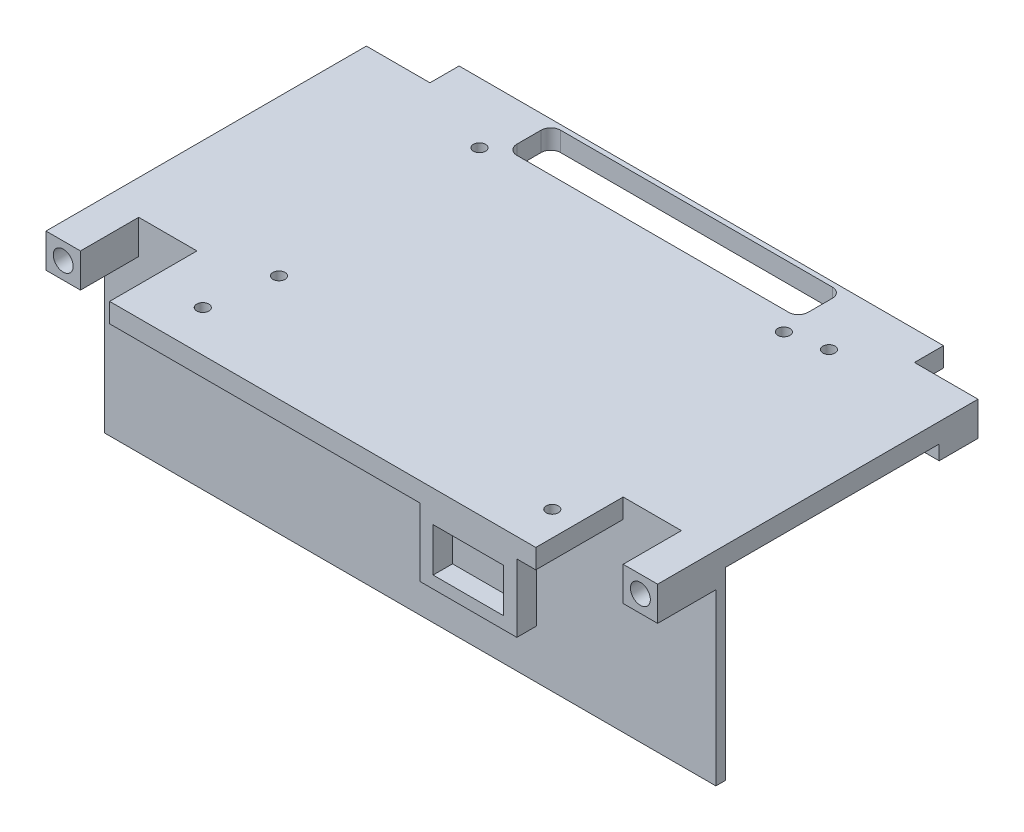
SolidWorks part; units mm, degrees
ref_plane "Front Plane" through (0, 0, 0) normal (0, 0, 1) x (1, 0, 0)
ref_plane "Top Plane" through (0, 0, 0) normal (0, 1, 0) x (1, 0, 0)
ref_plane "Right Plane" through (0, 0, 0) normal (1, 0, 0) x (0, 0, -1)
sketch "Sketch1" plane through (0, 0, 0) normal (0, 1, 0) x (1, 0, 0)
  line L0 (-63, 0) -> (63, 0) construction
  line L1 (-63, -33) -> (-55.9, -33)
  line L2 (-63, -33) -> (-63, 33)
  line L3 (-63, 33) -> (-55.9, 33)
  line L4 (63, -33) -> (63, 33)
  line L5 (-63, -33) -> (63, 33) construction
  line L6 (-63, 33) -> (63, -33) construction
  line L8 (-55.9, 33) -> (-55.9, 40)
  line L9 (-55.9, 40) -> (55.9, 40)
  line L10 (55.9, 33) -> (55.9, 40)
  line L11 (55.9, 33) -> (63, 33)
  line L12 (55.9, -33) -> (55.9, -40)
  line L13 (-55.9, -40) -> (55.9, -40)
  line L14 (-55.9, -33) -> (-55.9, -40)
  line L15 (55.9, -33) -> (63, -33)
  point P0 (0, 0)
  point P10 (0, 40)
  dimension "D1" = 126
  dimension "D2" = 66
  dimension "D3" = 7.1
  dimension "D4" = 7
extrude "Boss-Extrude1" add sketch "Sketch1" along normal blind 4
sketch "Sketch3" plane through (0, 0, 0) normal (0, -1, 0) x (1, 0, 0)
  line L0 (-63, -33) -> (-63, 33) construction
  line L1 (-55.9, -33) -> (-63, -33)
  line L2 (-55.9, -33) -> (-55.9, -25)
  line L3 (-55.9, -25) -> (-63, -25)
  line L4 (-63, -33) -> (-63, -25)
  dimension "D1" = 8
extrude "Boss-Extrude3" add sketch "Sketch3" along normal blind 3
sketch "Sketch4" plane through (0, 0, -33) normal (0, 0, -1) x (-1, 0, 0)
  line L0 (63, -3) -> (55.9, 4) construction
  circle A0 centre (59.45, 0.5) radius 2.05
  dimension "D1" = 4.1
extrude "Cut-Extrude1" cut sketch "Sketch4" against normal blind 7
mirror "Mirror1" about plane through (0, 0, 0) normal (1, 0, 0) of "Cut-Extrude1", "Boss-Extrude3"
mirror "Mirror2" about plane through (0, 0, 0) normal (0, 0, 1) of "Cut-Extrude1", "Boss-Extrude3", "Mirror1"
sketch "Sketch5" plane through (0, 4, 0) normal (0, 1, 0) x (1, 0, 0)
  line L0 (55.9, 40) -> (-55.9, 40) construction
  line L1 (-30, 38) -> (30, 38)
  line L2 (-30, 38) -> (-30, 29)
  line L3 (-30, 29) -> (30, 29)
  line L4 (30, 38) -> (30, 29)
  point P4 (0, 29)
  dimension "D1" = 2
  dimension "D2" = 9
  dimension "D3" = 60
extrude "Cut-Extrude2" cut sketch "Sketch5" against normal through all
sketch "Sketch6" plane through (0, 4, 0) normal (0, 1, 0) x (1, 0, 0)
  line L1 (-38.5, -28) -> (38.5, -28) construction
  line L2 (-38.5, -28) -> (-38.5, 24) construction
  line L3 (-38.5, 24) -> (38.5, 24) construction
  line L4 (38.5, -28) -> (38.5, 24) construction
  line L5 (-38.5, -28) -> (38.5, 24) construction
  line L6 (-38.5, 24) -> (38.5, -28) construction
  circle A0 centre (-38.5, 24) radius 1.25
  circle A1 centre (38.5, 24) radius 1.25
  circle A2 centre (38.5, -28) radius 1.25
  circle A3 centre (-38.5, -28) radius 1.25
  point P0 (0, -2)
  point P9 (0, -2)
  dimension "D4" = 2.5
  dimension "D1" = 77
  dimension "D2" = 52
  dimension "D3" = 2
fillet "Fillet1" radius 2 4 edges at (-30, 2, -38) (-30, 2, -29) (30, 2, -38) (30, 2, -29)
sketch "Sketch7" plane through (0, 4, 0) normal (0, 1, 0) x (1, 0, 0)
  line L0 (55.9, 33) -> (55.9, 40) construction
  line L1 (-55.9, 40) -> (55.9, 40)
  line L2 (-55.9, 40) -> (-55.9, 39)
  line L3 (-55.9, 39) -> (55.9, 39)
  line L4 (55.9, 40) -> (55.9, 39)
  line L5 (-55.9, -33) -> (-55.9, -40) construction
  line L6 (55.9, -40) -> (-55.9, -40)
  line L7 (55.9, -40) -> (55.9, -39)
  line L8 (55.9, -39) -> (-55.9, -39)
  line L9 (-55.9, -40) -> (-55.9, -39)
  dimension "D1" = 1
  dimension "D2" = 1
extrude "Cut-Extrude3" cut sketch "Sketch7" against normal through all
sketch "Sketch8" plane through (0, 0, 0) normal (0, -1, 0) x (1, 0, 0)
  line L0 (63, 25) -> (63, -25) construction
  line L1 (63, 21) -> (-63, 21)
  line L2 (63, 21) -> (63, 19)
  line L3 (63, 19) -> (-63, 19)
  line L4 (-63, 21) -> (-63, 19)
  line L5 (-63, -25) -> (-63, 25) construction
  line L7 (55.9, 39) -> (-55.9, 39) construction
  dimension "D1" = 20
  dimension "D2" = 2
extrude "Boss-Extrude4" add sketch "Sketch8" along normal blind 38
sketch "Sketch9" plane through (0, 4, 0) normal (0, 1, 0) x (1, 0, 0)
  line L0 (63, -21) -> (-63, -21) construction
  line L1 (-55.9, -39) -> (-43.9, -39)
  line L2 (-55.9, -39) -> (-55.9, -21)
  line L3 (-55.9, -21) -> (-43.9, -21)
  line L4 (-43.9, -39) -> (-43.9, -21)
  dimension "D1" = 12
extrude "Cut-Extrude4" cut sketch "Sketch9" against normal blind 10
sketch "Sketch10" plane through (0, -3, 0) normal (0, -1, 0) x (1, 0, 0)
  line L1 (-63, 25) -> (-55.9, 25)
  line L2 (-63, 25) -> (-63, 21)
  line L3 (-63, 21) -> (-55.9, 21)
  line L4 (-55.9, 25) -> (-55.9, 21)
  line L5 (55.9, 25) -> (63, 25)
  line L6 (55.9, 25) -> (55.9, 21)
  line L7 (55.9, 21) -> (63, 21)
  line L8 (63, 25) -> (63, 21)
extrude "Boss-Extrude5" add sketch "Sketch10" against normal up to surface (3 mm away) up to face at (29.4143, 0, 29)
ref_plane "Plane2" through (-56, 0, 0) normal (-1, 0, 0) x (0, 0, 1)
sketch "Sketch12" plane through (-56, 0, 0) normal (-1, 0, 0) x (0, 0, 1)
  line L0 (21, -5.8) -> (21, -16.2)
  line L1 (21, -38) -> (21, -3) construction
  line L2 (21, -16.2) -> (23.7, -13.5)
  line L3 (23.7, -13.5) -> (23.7, -8.5)
  line L4 (23.7, -8.5) -> (21, -5.8)
  line L5 (23.7, -11) -> (21, -11) construction
  line L6 (21, -3) -> (33, -3) construction
  line L7 (23.1, -9) -> (21.6, -9)
  line L8 (23.1, -9) -> (23.1, -13)
  line L9 (23.1, -13) -> (21.6, -13)
  line L10 (21.6, -9) -> (21.6, -13)
  line L11 (21, -20.8) -> (21, -31.2)
  line L12 (21, -31.2) -> (23.7, -28.5)
  line L13 (23.7, -28.5) -> (23.7, -23.5)
  line L14 (23.7, -23.5) -> (21, -20.8)
  line L15 (23.1, -24) -> (21.6, -24)
  line L16 (23.1, -24) -> (23.1, -28)
  line L17 (23.1, -28) -> (21.6, -28)
  line L18 (21.6, -24) -> (21.6, -28)
  line L19 (23.7, -26) -> (21, -26) construction
  point P13 (22.35, -11)
  point P14 (23.1, -11)
  dimension "D1" = 1.5
  dimension "D2" = 0.6
  dimension "D3" = 0.6
  dimension "D4" = 4
  dimension "D5" = 45
  dimension "D6" = 5
  dimension "D7" = 8
  dimension "D8" = 2
extrude "Boss-Extrude6" add sketch "Sketch12" against normal blind 2
ref_plane "Plane3" through (-49.9, 0, 0) normal (1, 0, 0) x (0, 0, -1)
mirror "Mirror3" about plane through (-49.9, 0, 0) normal (1, 0, 0) of "Boss-Extrude6"
sketch "Sketch13" plane through (0, 0, 0) normal (0, -1, 0) x (1, 0, 0)
  line L0 (-28, -29) -> (28, -29) construction
  line L1 (-20, -19.5) -> (20, -19.5)
  line L2 (-20, -19.5) -> (-20, -21.5)
  line L3 (-20, -21.5) -> (20, -21.5)
  line L4 (20, -19.5) -> (20, -21.5)
  point P4 (0, -21.5)
  dimension "D1" = 40
  dimension "D2" = 2
  dimension "D3" = 7.5
extrude "Boss-Extrude7" add sketch "Sketch13" along normal up to surface (38 mm away) up to face at (0, -38, 20)
sketch "Sketch14" plane through (0, 0, 0) normal (1, 0, 0) x (0, 0, -1)
  line L0 (-19, -19) -> (19.5, -19) construction
  line L1 (-19, -38) -> (-19, 0) construction
  line L2 (19.5, -38) -> (19.5, 0) construction
  line L3 (0.25, -38) -> (0.25, 0) construction
  line L4 (-19, 0) -> (25, 0) construction
  line L5 (-21, -31.2) -> (-23.7, -28.5) construction
  line L6 (-23.1, -24) -> (-21.6, -24) construction
  line L7 (-23.1, -28) -> (-23.1, -24) construction
  line L8 (-21.6, -28) -> (-23.1, -28) construction
  line L9 (-21.6, -24) -> (-21.6, -28) construction
  line L10 (-21, -20.8) -> (-21, -31.2) construction
  line L11 (-23.7, -23.5) -> (-21, -20.8) construction
  line L12 (-23.7, -28.5) -> (-23.7, -23.5) construction
  line L13 (-23.1, -13) -> (-23.1, -9) construction
  line L14 (-23.1, -9) -> (-21.6, -9) construction
  line L15 (-21.6, -9) -> (-21.6, -13) construction
  line L16 (-21.6, -13) -> (-23.1, -13) construction
  line L17 (-21, -5.8) -> (-21, -16.2) construction
  line L18 (-21, -16.2) -> (-23.7, -13.5) construction
  line L19 (-23.7, -13.5) -> (-23.7, -8.5) construction
  line L20 (-23.7, -8.5) -> (-21, -5.8) construction
  line L21 (-21, -31.2) -> (-23.7, -28.5) construction
  line L22 (-23.1, -24) -> (-21.6, -24) construction
  line L23 (-23.1, -28) -> (-23.1, -24) construction
  line L24 (-21.6, -28) -> (-23.1, -28) construction
  line L25 (-21.6, -24) -> (-21.6, -28) construction
  line L26 (-21, -20.8) -> (-21, -31.2) construction
  line L27 (-23.7, -23.5) -> (-21, -20.8) construction
  line L28 (-23.7, -28.5) -> (-23.7, -23.5) construction
  line L29 (-23.1, -13) -> (-23.1, -9) construction
  line L30 (-23.1, -9) -> (-21.6, -9) construction
  line L31 (-21.6, -9) -> (-21.6, -13) construction
  line L32 (-21.6, -13) -> (-23.1, -13) construction
  line L33 (-21, -5.8) -> (-21, -16.2) construction
  line L34 (-21, -16.2) -> (-23.7, -13.5) construction
  line L35 (-23.7, -13.5) -> (-23.7, -8.5) construction
  line L36 (-23.7, -8.5) -> (-21, -5.8) construction
  line L37 (24.2, -8.5) -> (21.5, -5.8)
  line L38 (24.2, -13.5) -> (24.2, -8.5)
  line L39 (21.5, -16.2) -> (24.2, -13.5)
  line L40 (21.5, -5.8) -> (21.5, -16.2)
  line L41 (22.1, -13) -> (23.6, -13)
  line L42 (22.1, -9) -> (22.1, -13)
  line L43 (23.6, -9) -> (22.1, -9)
  line L44 (23.6, -13) -> (23.6, -9)
  line L45 (24.2, -28.5) -> (24.2, -23.5)
  line L46 (24.2, -23.5) -> (21.5, -20.8)
  line L47 (21.5, -20.8) -> (21.5, -31.2)
  line L48 (22.1, -24) -> (22.1, -28)
  line L49 (22.1, -28) -> (23.6, -28)
  line L50 (23.6, -28) -> (23.6, -24)
  line L51 (23.6, -24) -> (22.1, -24)
  line L52 (21.5, -31.2) -> (24.2, -28.5)
  point P11 (0.25, -19)
extrude "Boss-Extrude8" add sketch "Sketch14" along normal mid plane 2
sketch "Sketch15" plane through (0, 0, 0) normal (1, 0, 0) x (0, 0, -1)
  line L0 (19.5, 0) -> (19.5, -5)
  line L1 (19.5, -38) -> (19.5, 0) construction
  line L2 (19.5, -5) -> (16.6132, 0)
  line L3 (-19, 0) -> (25, 0) construction
  line L4 (16.6132, 0) -> (19.5, 0)
  dimension "D1" = 60
  dimension "D2" = 5
extrude "Boss-Extrude9" add sketch "Sketch15" against normal up to surface and the other way up to surface up to face at (-20, -19, -20.5) other way up to face at (20, -19, -20.5)
sketch "Sketch16" plane through (0, 0, 39) normal (0, 0, 1) x (1, 0, 0)
  line L0 (40, 0) -> (20, -14) construction
  line L1 (40, 0) -> (20, 0)
  line L2 (40, 0) -> (40, -14)
  line L3 (40, -14) -> (20, -14)
  line L4 (20, 0) -> (20, -14)
  line L5 (55.9, 0) -> (-43.9, 0) construction
  line L6 (22.75, -2.5) -> (37.25, -2.5)
  line L7 (22.75, -2.5) -> (22.75, -11.5)
  line L8 (22.75, -11.5) -> (37.25, -11.5)
  line L9 (37.25, -2.5) -> (37.25, -11.5)
  line L10 (22.75, -2.5) -> (37.25, -11.5) construction
  line L11 (22.75, -11.5) -> (37.25, -2.5) construction
  line L12 (63, -38) -> (63, -3) construction
  point P5 (30, -7)
  dimension "D1" = 20
  dimension "D2" = 14
  dimension "D3" = 14.5
  dimension "D4" = 9
  dimension "D5" = 23
extrude "Boss-Extrude10" add sketch "Sketch16" against normal blind 4
sketch "Sketch17" plane through (0, 0, 0) normal (0, -1, 0) x (1, 0, 0)
  line L6 (-43.9, 21) -> (-55.9, 21) construction
  line L7 (55.9, 39) -> (43.9, 39)
  line L8 (55.9, 39) -> (55.9, 21)
  line L9 (55.9, 21) -> (43.9, 21)
  line L10 (43.9, 39) -> (43.9, 21)
  line L13 (-43.9, 39) -> (-43.9, 21) construction
extrude "Cut-Extrude5" cut sketch "Sketch17" against normal through all
sketch "Sketch18" plane through (0, 4, 0) normal (0, 1, 0) x (1, 0, 0)
  line L5 (-55.9, 39) -> (55.9, 39) construction
  line L6 (55.9, 33) -> (49.9, 33)
  line L7 (55.9, 33) -> (55.9, 39)
  line L8 (55.9, 39) -> (49.9, 39)
  line L9 (49.9, 33) -> (49.9, 39)
  line L11 (-55.9, 33) -> (-49.9, 33)
  line L12 (-55.9, 33) -> (-55.9, 39)
  line L13 (-55.9, 39) -> (-49.9, 39)
  line L14 (-49.9, 33) -> (-49.9, 39)
extrude "Cut-Extrude6" cut sketch "Sketch18" against normal through all
sketch "Sketch20" plane through (0, 4, 0) normal (0, 1, 0) x (1, 0, 0)
  line L0 (-31, 25) -> (31, -17) construction
  line L1 (-31, 25) -> (31, 25) construction
  line L2 (-31, 25) -> (-31, -17) construction
  line L3 (-31, -17) -> (31, -17) construction
  line L4 (31, 25) -> (31, -17) construction
  line L5 (-38.5, 26) -> (38.5, 26) construction
  line L6 (-38.5, 26) -> (-38.5, -26) construction
  line L7 (-38.5, -26) -> (38.5, -26) construction
  line L8 (38.5, 26) -> (38.5, -26) construction
  line L11 (38.5, 26) -> (-38.5, -26) construction
  circle A0 centre (-31, 25) radius 3 construction
  circle A1 centre (-31, -17) radius 3 construction
  circle A2 centre (31, -17) radius 3 construction
  circle A3 centre (31, 25) radius 3 construction
  circle A4 centre (-38.5, 26) radius 3 construction
  circle A5 centre (38.5, 26) radius 3 construction
  circle A6 centre (38.5, -26) radius 3 construction
  circle A7 centre (-38.5, -26) radius 3 construction
  point P18 (0, 4)
  dimension "D3" = 6
  dimension "D1" = 42
  dimension "D2" = 62
  dimension "D4" = 4
  dimension "D6" = 77
  dimension "D7" = 52
sketch "Sketch22" plane through (0, 4, 0) normal (0, 1, 0) x (1, 0, 0)
  circle A0 centre (-31, 25) radius 1.25 construction
  circle A1 centre (31, 25) radius 1.25
  circle A2 centre (31, -17) radius 1.25 construction
  circle A3 centre (-31, -17) radius 1.25
  dimension "D1" = 2.5
extrude "Cut-Extrude7" cut sketch "Sketch22" against normal up to surface (4 mm away) up to face at (15, 0, 33.5)
sketch "Sketch25" plane through (0, 0, -21.5) normal (0, 0, -1) x (-1, 0, 0)
  line L0 (63, -38) -> (-63, -38) construction
  line L1 (-20, -38) -> (-14, -38)
  line L2 (-20, -38) -> (-20, 0)
  line L3 (-20, 0) -> (-14, 0)
  line L4 (-14, -38) -> (-14, 0)
  line L5 (-20, -38) -> (-20, 0) construction
  line L6 (20, 0) -> (-20, 0) construction
  line L7 (-20, -38) -> (20, -38) construction
  line L8 (20, 0) -> (14, 0)
  line L9 (20, 0) -> (20, -38)
  line L10 (20, -38) -> (14, -38)
  line L11 (14, 0) -> (14, -38)
  dimension "D1" = 6
extrude "Cut-Extrude11" cut sketch "Sketch25" against normal blind 10
sketch "Sketch26" plane through (-1, 0, 0) normal (-1, 0, 0) x (0, 0, 1)
  line L1 (-21.5, -5.8) -> (-27.2016, -5.8)
  line L2 (-21.5, -5.8) -> (-21.5, -36.3625)
  line L3 (-21.5, -36.3625) -> (-27.2016, -36.3625)
  line L4 (-27.2016, -5.8) -> (-27.2016, -36.3625)
  line L5 (21, -5.8) -> (28.5342, -5.8)
  line L6 (21, -5.8) -> (21, -34.3243)
  line L7 (21, -34.3243) -> (28.5342, -34.3243)
  line L8 (28.5342, -5.8) -> (28.5342, -34.3243)
extrude "Cut-Extrude12" cut sketch "Sketch26" against normal through all both and the other way through all
sketch "Sketch27" plane through (0, 4, 0) normal (0, 1, 0) x (1, 0, 0)
  line L1 (-33.2, -30.5) -> (38.8, -30.5) construction
  line L2 (-33.2, -30.5) -> (-33.2, 26.5) construction
  line L3 (-33.2, 26.5) -> (38.8, 26.5) construction
  line L4 (38.8, -30.5) -> (38.8, 26.5) construction
  line L5 (-33.2, -30.5) -> (38.8, 26.5) construction
  line L6 (-33.2, 26.5) -> (38.8, -30.5) construction
  circle A0 centre (-33.2, 26.5) radius 1.25
  circle A1 centre (-33.2, -30.5) radius 1.25
  circle A2 centre (38.8, -30.5) radius 1.25
  circle A3 centre (38.8, 26.5) radius 1.25
  circle A5 centre (31, 25) radius 1.25 construction
  circle A6 centre (31, 25) radius 1.25 construction
  point P0 (2.8, -2)
  point P12 (1.0635, -1.6938)
  dimension "D1" = 72
  dimension "D2" = 57
  dimension "D3" = 2
  dimension "D4" = 2.8
extrude "Cut-Extrude13" cut sketch "Sketch27" against normal through all
